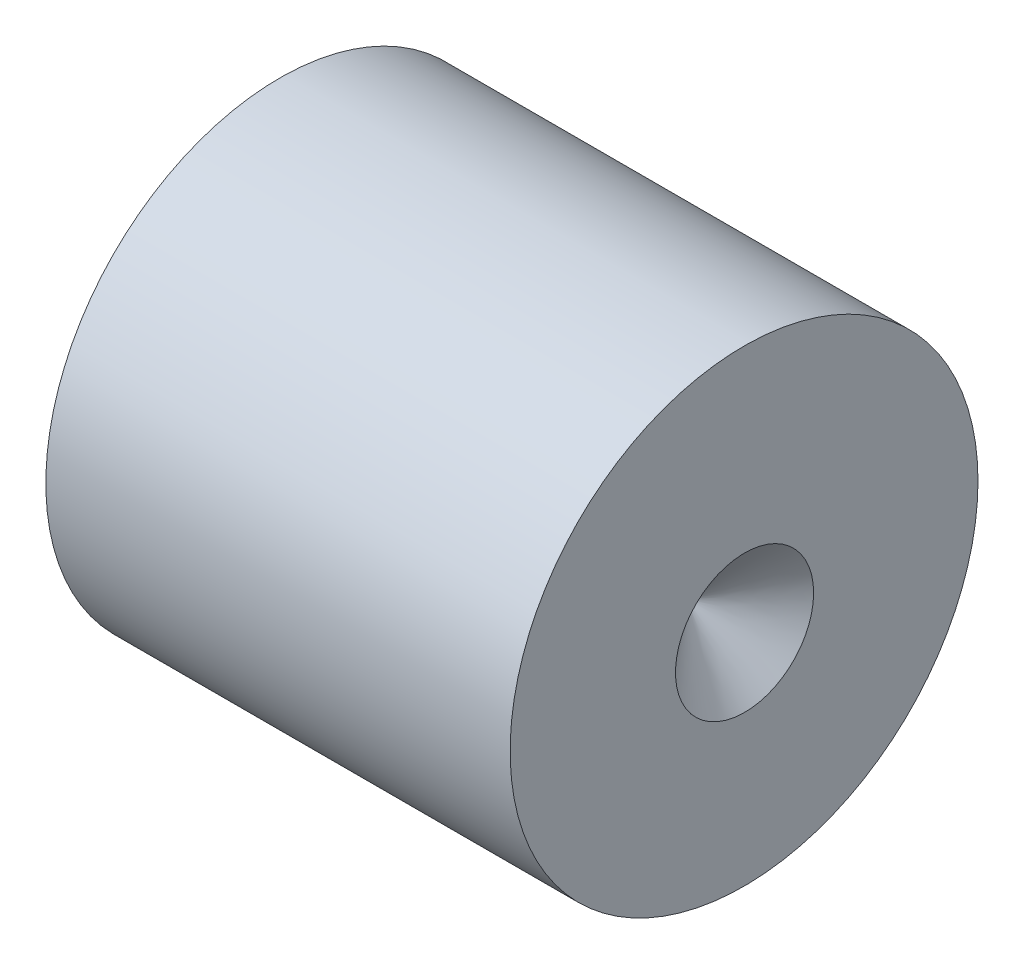
SolidWorks part; units mm, degrees
ref_plane "Front Plane" through (0, 0, 0) normal (0, 0, 1) x (1, 0, 0)
ref_plane "Top Plane" through (0, 0, 0) normal (0, 1, 0) x (1, 0, 0)
ref_plane "Right Plane" through (0, 0, 0) normal (1, 0, 0) x (0, 0, -1)
sketch "Sketch1" plane through (0, 0, 0) normal (1, 0, 0) x (0, 0, -1)
  circle A0 centre (-7.978, 45.8221) radius 5.1191
  dimension "D1" = 10.2381
extrude "Boss-Extrude1" add sketch "Sketch1" along normal blind 10.16
hole_wizard "#97 (0.0059) Diameter Hole1" positions "Sketch2" profile "Sketch3" hole size "#97" standard "ANSI Inch"
sketch "Sketch2" plane through (10.16, 0, 0) normal (1, 0, 0) x (0, 0, -1)
  line L0 (-3.1652, 76.052) -> (-13.2037, 76.052) construction
  point P0 (-7.967, 45.5024)
  point P2 (-8.1845, 76.052)
  point P6 (-8.2648, 76.5081)
  point P9 (-7.967, 45.5024)
sketch "Sketch3" plane through (10.16, 45.5024, 7.967) normal (0, 1, 0) x (0, 0, -1)
  line L0 (0, 0) -> (0, 4.109)
  line L1 (0, 4.109) -> (0.0749, 4.064)
  line L2 (0.0749, 4.064) -> (0.0749, 1.2053)
  line L3 (0.0749, 1.2053) -> (1.5113, 0)
  line L5 (1.5113, 0) -> (0, 0)
  line L6 (-0.0749, 1.2053) -> (-1.5113, 0) construction
  line L10 (0, 4.109) -> (-0.0749, 4.064) construction
  line L11 (0, -6.35) -> (0, 107.95) construction
  dimension "Hole Dia." = 0.1499
  dimension "Hole Depth" = 4.064
  dimension "Near C'Sink Dia." = 3.0226
  dimension "Near C'Sink Angle" = 100
  dimension "Drill Angle" = 118
hole_wizard "#97 (0.0059) Diameter Hole2" positions "Sketch6" profile "Sketch7" hole size "#97" standard "ANSI Inch"
sketch "Sketch6" plane through (0, 0, 0) normal (-1, 0, 0) x (0, 0, 1)
  point P0 (8.0545, 45.6055)
  point P2 (7.8357, 14.9835)
sketch "Sketch7" plane through (0, 45.6055, 8.0545) normal (0, 1, 0) x (0, 0, 1)
  line L0 (0, 0) -> (0, 4.109)
  line L1 (0, 4.109) -> (0.0749, 4.064)
  line L2 (0.0749, 4.064) -> (0.0749, 1.2053)
  line L3 (0.0749, 1.2053) -> (1.5113, 0)
  line L5 (1.5113, 0) -> (0, 0)
  line L6 (-0.0749, 1.2053) -> (-1.5113, 0) construction
  line L10 (0, 4.109) -> (-0.0749, 4.064) construction
  line L11 (0, -6.35) -> (0, 107.95) construction
  dimension "Hole Dia." = 0.1499
  dimension "Hole Depth" = 4.064
  dimension "Near C'Sink Dia." = 3.0226
  dimension "Near C'Sink Angle" = 100
  dimension "Drill Angle" = 118
